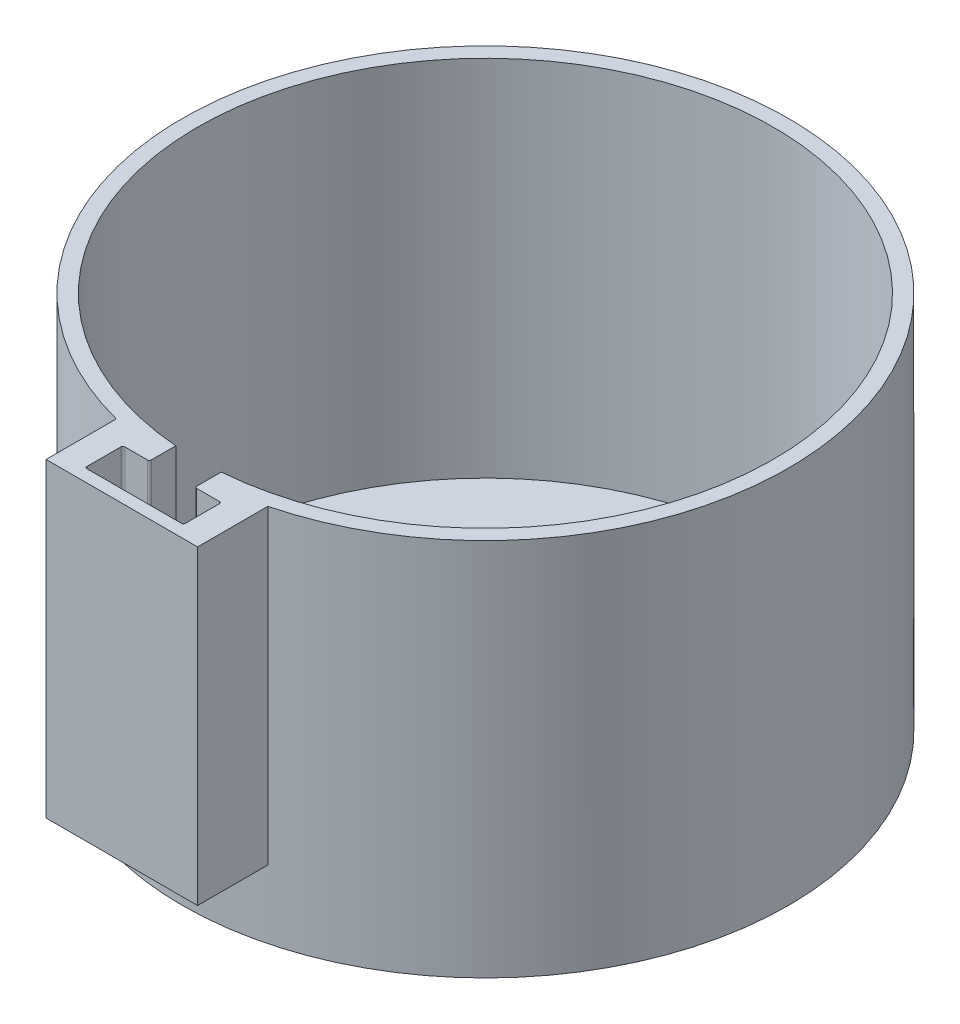
SolidWorks part; units mm, degrees
ref_plane "Front Plane" through (0, 0, 0) normal (0, 0, 1) x (1, 0, 0)
ref_plane "Top Plane" through (0, 0, 0) normal (0, 1, 0) x (1, 0, 0)
ref_plane "Right Plane" through (0, 0, 0) normal (1, 0, 0) x (0, 0, -1)
sketch "Sketch1" plane through (0, 0, 0) normal (0, 1, 0) x (1, 0, 0)
  circle A0 centre (0, 0) radius 40
extrude "Boss-Extrude1" add sketch "Sketch1" along normal blind 40 contours A0
sketch "Sketch2" plane through (0, 40, 0) normal (0, 1, 0) x (1, 0, 0)
  circle A0 centre (0, 0) radius 38
extrude "Cut-Extrude1" cut sketch "Sketch2" against normal blind 38
sketch "Sketch3" plane through (0, 2, 0) normal (0, 1, 0) x (1, 0, 0)
  line L0 (-38, 0) -> (38, 0) construction
  circle A1 centre (0, 0) radius 38 construction
  circle A2 centre (0, 0) radius 38 construction
  arc A4 (-14.0761, -35.2968) -> (14.0761, -35.2968) centre (0, -39.1212) cw
  arc A5 (-14.0761, -35.2968) -> (14.0761, -35.2968) centre (0, 0) ccw
extrude "Cut-Extrude2" cut sketch "Sketch3" against normal blind 38
sketch "Sketch4" plane through (0, 2, 0) normal (0, 1, 0) x (1, 0, 0)
  circle A0 centre (0, 0) radius 5
extrude "Cut-Extrude3" cut sketch "Sketch4" against normal blind 38
sketch "Sketch6" plane through (0, 0, 0) normal (0, -1, 0) x (1, 0, 0)
  circle A1 centre (-20, 0) radius 2
  circle A2 centre (20, 0) radius 2
extrude "Boss-Extrude2" add sketch "Sketch6" along normal blind 2
sketch "Sketch8" plane through (0, 40, 0) normal (0, 1, 0) x (1, 0, 0)
  circle A0 centre (0, 0) radius 43.4969
sketch "Sketch9" plane through (0, 40, 0) normal (0, 1, 0) x (1, 0, 0)
  circle A3 centre (0, 0) radius 40
  circle A4 centre (0, 0) radius 40
  circle A6 centre (0, 0) radius 38 construction
  circle A7 centre (0, 0) radius 38
  dimension "D1" = 0
extrude "Boss-Extrude3" add sketch "Sketch9" along normal blind 10
sketch "Sketch10" plane through (0, 50, 0) normal (0, 1, 0) x (1, 0, 0)
  line L0 (0, 0) -> (0, -38) construction
  line L4 (0, -38) -> (10, -38)
  line L6 (10, -38) -> (10, -48)
  line L8 (0, -38) -> (-10, -38)
  line L9 (-10, -38) -> (-10, -48)
  line L10 (-10, -48) -> (10, -48)
  circle A0 centre (0, 0) radius 38 construction
extrude "Boss-Extrude4" add sketch "Sketch10" against normal blind 41 contours L8 L9 L10 L6 L4
sketch "Sketch11" plane through (0, 50, 0) normal (0, 1, 0) x (1, 0, 0)
  line L0 (0, -48) -> (0, -38) construction
  line L1 (-10, -48) -> (10, -48) construction
  line L2 (-10, -43.3649) -> (10, -43.3649) construction
  line L3 (-10, -38.7298) -> (-10, -48) construction
  line L4 (10, -38.7298) -> (10, -48) construction
  line L8 (-3, -36.8649) -> (3, -36.8649)
  line L10 (-3, -36.8649) -> (-3, -41.3649)
  line L11 (3, -36.8649) -> (3, -41.3649)
  line L12 (3, -41.3649) -> (6.5, -41.3649)
  line L13 (6.5, -41.3649) -> (6.5, -46.3649)
  line L14 (-3, -41.3649) -> (-6.5, -41.3649)
  line L15 (-6.5, -41.3649) -> (-6.5, -46.3649)
  line L16 (-6.5, -46.3649) -> (6.5, -46.3649)
  arc A0 (14.0761, -35.2968) -> (-14.0761, -35.2968) centre (0, 0) ccw construction
  dimension "D1" = 13
  dimension "D2" = 5
  dimension "D3" = 4.5
  dimension "D4" = 6
extrude "Cut-Extrude4" cut sketch "Sketch11" against normal blind 39
fillet "Fillet1" radius 0.25 6 edges at (-3, 30.5, 41.3649) (3, 30.5, 41.3649) (6.5, 30.5, 41.3649) (-6.5, 30.5, 41.3649) (6.5, 30.5, 46.3649) (-6.5, 30.5, 46.3649)
sketch "Sketch13" plane through (0, 0, 0) normal (0, -1, 0) x (1, 0, 0)
  circle A0 centre (-30, 0) radius 3
  circle A1 centre (30, 0) radius 3
extrude "Cut-Extrude5" cut sketch "Sketch13" against normal blind 10
